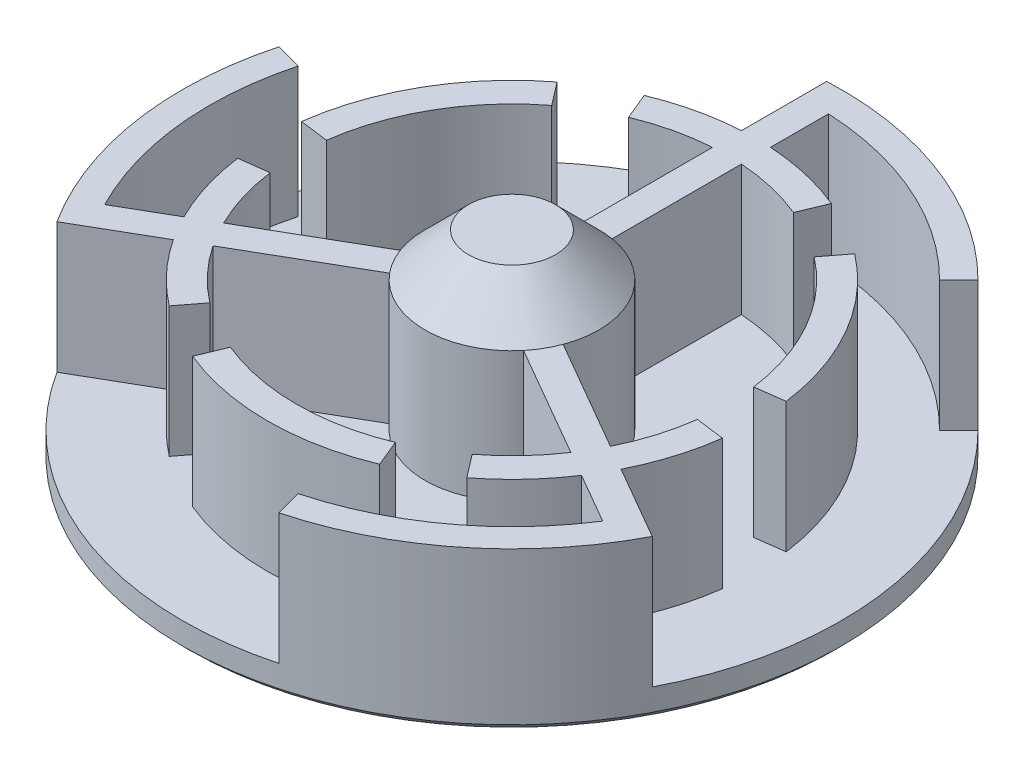
SolidWorks part; units mm, degrees
material "PLA"
ref_plane "Front Plane" through (0, 0, 0) normal (0, 0, 1) x (1, 0, 0)
ref_plane "Top Plane" through (0, 0, 0) normal (0, 1, 0) x (1, 0, 0)
ref_plane "Right Plane" through (0, 0, 0) normal (1, 0, 0) x (0, 0, -1)
sketch "Sketch1" plane through (0, 0, 0) normal (0, 1, 0) x (1, 0, 0)
  circle A0 centre (0, 0) radius 36.115
  dimension "D1" = 72.23
extrude "Boss-Extrude1" add sketch "Sketch1" along normal blind 3.175
sketch "Sketch2" plane through (0, 3.175, 0) normal (0, 1, 0) x (1, 0, 0)
  circle A0 centre (0, 0) radius 9.525
  dimension "D1" = 19.05
extrude "Boss-Extrude3" add sketch "Sketch2" along normal blind 19.05
chamfer "Chamfer1" distance 4.7625 angle 45 1 edges at (0, 22.225, 9.525)
sketch "Sketch5" plane through (0, 0, 0) normal (0, -1, 0) x (1, 0, 0)
  circle A0 centre (0, 0) radius 15.875
  dimension "D1" = 31.75
extrude "Boss-Extrude4" add sketch "Sketch5" along normal blind 11.9062
sketch "Sketch6" plane through (0, 3.175, 0) normal (0, 1, 0) x (1, 0, 0)
  line L1 (1.5875, 0) -> (1.5875, 1.5875)
  line L2 (-1.5875, 9.3918) -> (-1.5875, 36.3141)
  line L3 (0, 0) -> (1.5875, 0) construction
  line L4 (0, 0) -> (1.5875, 1.5875)
  line L5 (23.4329, 23.4329) -> (25.6779, 25.6779)
  line L6 (1.5875, 9.3918) -> (1.5875, 33.101)
  line L10 (1.5875, 36.2793) -> (1.5875, 36.3141)
  arc A0 (25.6779, 25.6779) -> (-1.5875, 36.2793) centre (0, 0) ccw
  arc A1 (25.6779, 25.6779) -> (-1.5875, 36.2793) centre (0, 0) ccw
  arc A3 (1.5875, 9.3918) -> (-1.5875, 9.3918) centre (0, 0) ccw
  arc A4 (23.4329, 23.4329) -> (1.5875, 33.101) centre (0, 0) ccw
  circle A5 centre (0, 0) radius 33.1391 construction
  circle A6 centre (0, 0) radius 36.3141 construction
  dimension "D3" = 3.175
extrude "Boss-Extrude5" add sketch "Sketch6" along normal blind 14.2875 contours A4 L5 L2 L1 L6
pattern_circular "CirPattern1" count 3 over 360 about axis through (0, 22.225, 0) along (0, -1, 0) of "Boss-Extrude5"
sketch "Sketch8" plane through (0, 3.175, 0) normal (0, 1, 0) x (1, 0, 0)
  line L0 (23.6141, 0) -> (26.7891, 0)
  line L1 (20.4504, 11.807) -> (26.4886, 15.2932) construction
  line L2 (14.3753, 18.7343) -> (16.3081, 21.2532)
  line L3 (23.412, 3.0823) -> (26.5599, 3.4967)
  arc A1 (23.6141, 0) -> (14.3753, 18.7343) centre (0, 0) ccw
  arc A2 (26.7891, 0) -> (16.3081, 21.2532) centre (0, 0) ccw
  circle A3 centre (0, 0) radius 26.7891 construction
  circle A4 centre (0, 0) radius 23.6141 construction
  dimension "D1" = 30
  dimension "D3" = 22.5
  dimension "D4" = 22.5
  dimension "D2" = 3.175
extrude "Boss-Extrude6" add sketch "Sketch8" along normal blind 14.2875 contours L3 A2 L2 A1
pattern_circular "CirPattern2" count 6 over 360 about axis through (0, 0, 0) along (0, 1, 0) of "Boss-Extrude6"
sketch "Sketch9" plane through (0, -11.9062, 0) normal (0, -1, 0) x (1, 0, 0)
  circle A2 centre (0, 0) radius 13.335
  circle A3 centre (0, 0) radius 13.335
  dimension "D1" = 2.54
extrude "Cut-Extrude1" cut sketch "Sketch9" against normal up to surface (11.9062 mm away) up to face at (0, 0, -15.875)
chamfer "Chamfer2" distance 0.762 angle 45 1 edges at (0, 0, 36.115)
chamfer "Chamfer3" distance 0.762 angle 45 1 edges at (0, -11.9062, -15.875)
